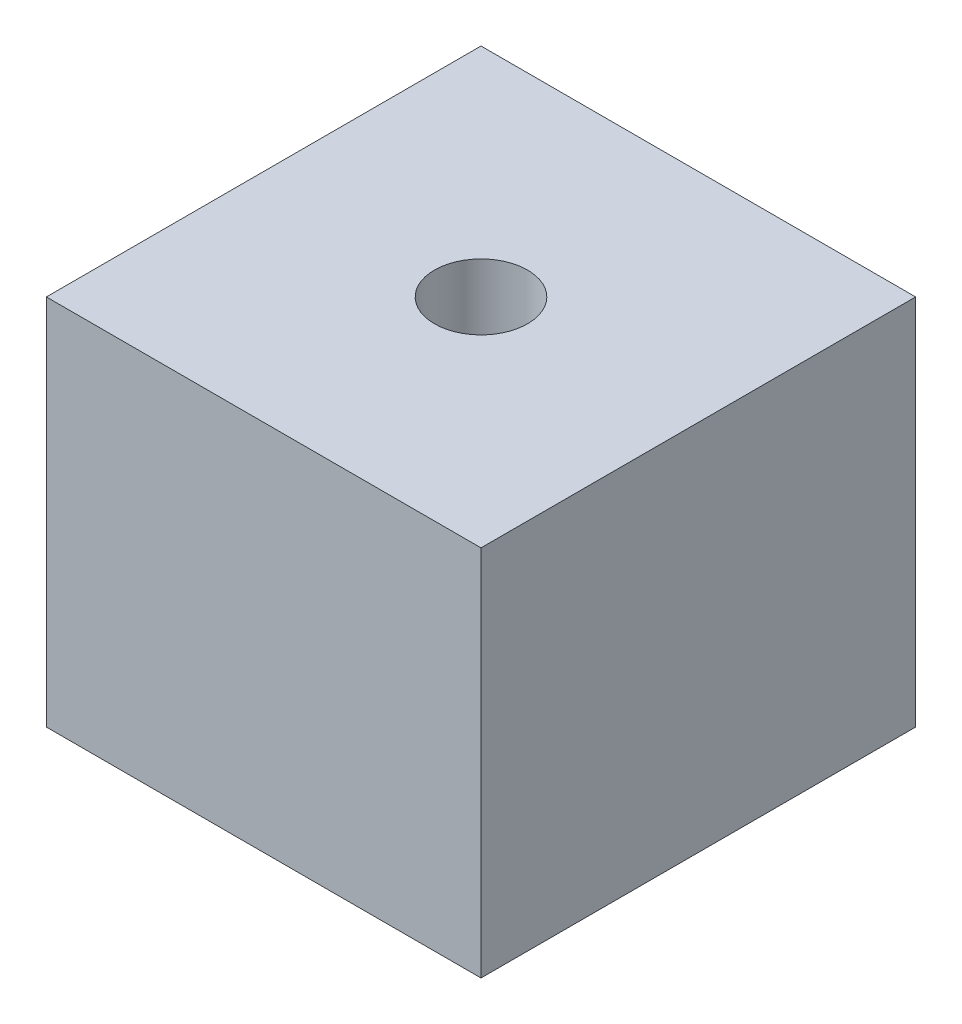
SolidWorks part; units mm, degrees
ref_plane "Front Plane" through (0, 0, 0) normal (0, 0, 1) x (1, 0, 0)
ref_plane "Top Plane" through (0, 0, 0) normal (0, 1, 0) x (1, 0, 0)
ref_plane "Right Plane" through (0, 0, 0) normal (1, 0, 0) x (0, 0, -1)
sketch "Sketch1" plane through (0, 0, 0) normal (0, 1, 0) x (1, 0, 0)
  line L1 (0, 0) -> (88.9, 0)
  line L2 (0, 0) -> (0, -88.9)
  line L3 (0, -88.9) -> (88.9, -88.9)
  line L4 (88.9, 0) -> (88.9, -88.9)
  dimension "D1" = 88.9
  dimension "D2" = 88.9
extrude "Boss-Extrude1" add sketch "Sketch1" along normal blind 76.2 contours L1 L4 L3 L2
sketch "Sketch2" plane through (0, 76.2, 0) normal (0, 1, 0) x (1, 0, 0)
  line L0 (44.45, 0) -> (44.45, -88.9) construction
  line L1 (0, 0) -> (88.9, 0) construction
  line L2 (0, -88.9) -> (88.9, -88.9) construction
  circle A0 centre (44.45, -44.45) radius 9.525
  dimension "D1" = 19.05
extrude "Cut-Extrude1" cut sketch "Sketch2" against normal blind 38.1 contours A0
